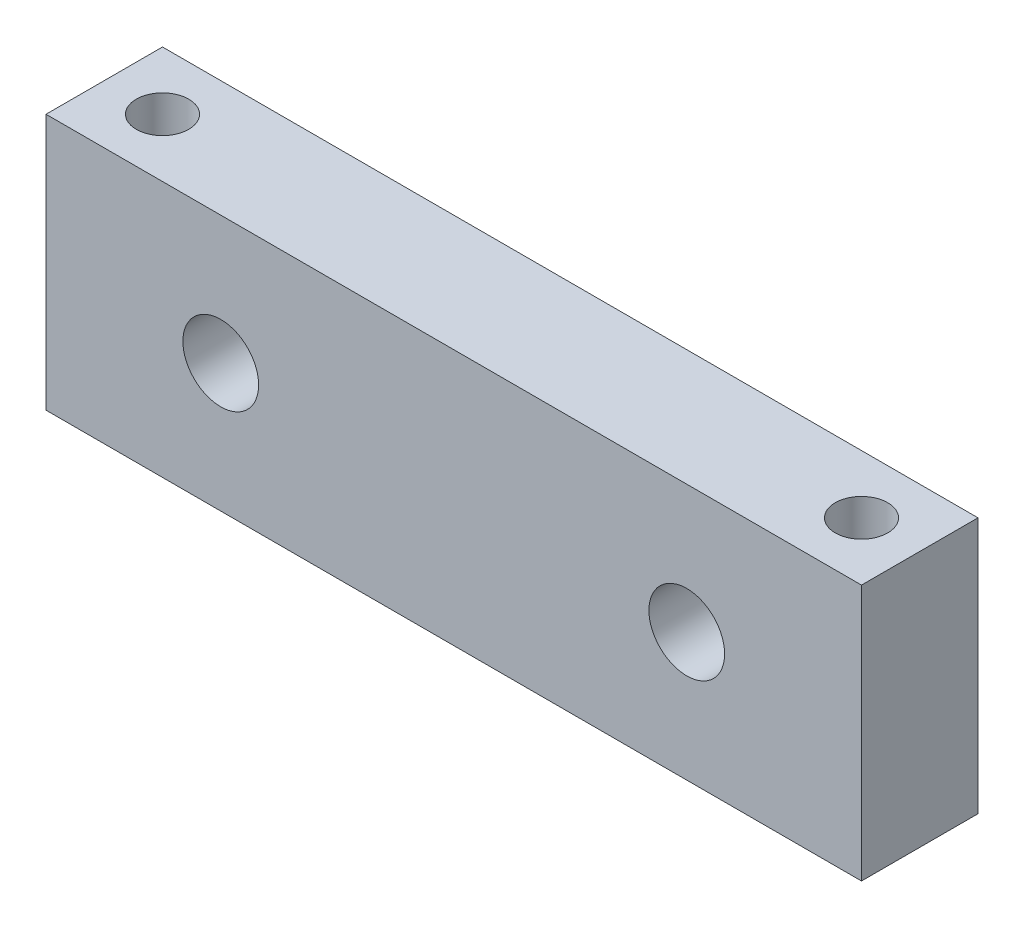
SolidWorks part; units mm, degrees
ref_plane "Front Plane" through (0, 0, 0) normal (0, 0, 1) x (1, 0, 0)
ref_plane "Top Plane" through (0, 0, 0) normal (0, 1, 0) x (1, 0, 0)
ref_plane "Right Plane" through (0, 0, 0) normal (1, 0, 0) x (0, 0, -1)
sketch "Sketch1" plane through (0, 0, 0) normal (0, 0, 1) x (1, 0, 0)
  line L1 (-35, -11) -> (35, -11)
  line L2 (-35, -11) -> (-35, 11)
  line L3 (-35, 11) -> (35, 11)
  line L4 (35, -11) -> (35, 11)
  line L5 (-35, -11) -> (35, 11) construction
  line L6 (-35, 11) -> (35, -11) construction
  point P0 (0, 0)
  dimension "D1" = 70
  dimension "D2" = 22
extrude "Boss-Extrude1" add sketch "Sketch1" along normal blind 10
sketch "Sketch2" plane through (0, 11, 0) normal (0, 1, 0) x (1, 0, 0)
  line L0 (0, -5) -> (-35, -5) construction
  line L3 (0, 0) -> (0, -10) construction
  line L4 (35, 0) -> (-35, 0) construction
  line L5 (35, -10) -> (-35, -10) construction
  line L6 (-35, -10) -> (-35, 0) construction
  circle A0 centre (-30, -5) radius 2.25
  circle A1 centre (30, -5) radius 2.25
  dimension "D2" = 4.5
  dimension "D1" = 30
extrude "Cut-Extrude1" cut sketch "Sketch2" against normal blind 45
sketch "Sketch3" plane through (0, 0, 10) normal (0, 0, 1) x (1, 0, 0)
  line L0 (0, 11) -> (0, -11) construction
  line L1 (35, 11) -> (-35, 11) construction
  line L2 (-35, -11) -> (35, -11) construction
  line L3 (0, 0) -> (20, 0) construction
  circle A0 centre (20, 0) radius 3.25
  circle A1 centre (-20, 0) radius 3.25
  dimension "D1" = 6.5
  dimension "D2" = 20
extrude "Cut-Extrude2" cut sketch "Sketch3" against normal blind 45
sketch "Sketch4" plane through (0, 0, 0) normal (0, 0, -1) x (-1, 0, 0)
  circle A0 centre (-20, 0) radius 3.1996
  circle A1 centre (-20, 0) radius 5.1996
  circle A2 centre (20, 0) radius 3.25
  circle A3 centre (20, 0) radius 5.25
  dimension "D1" = 2
  dimension "D2" = 2
extrude "Boss-Extrude2" add sketch "Sketch4" along normal blind 4
sketch "Sketch5" plane through (0, -11, 0) normal (0, -1, 0) x (1, 0, 0)
  circle A0 centre (30, 5) radius 4
  circle A1 centre (-30, 5) radius 4
  dimension "D1" = 8
  dimension "D2" = 8
extrude "Cut-Extrude3" cut sketch "Sketch5" against normal blind 4
